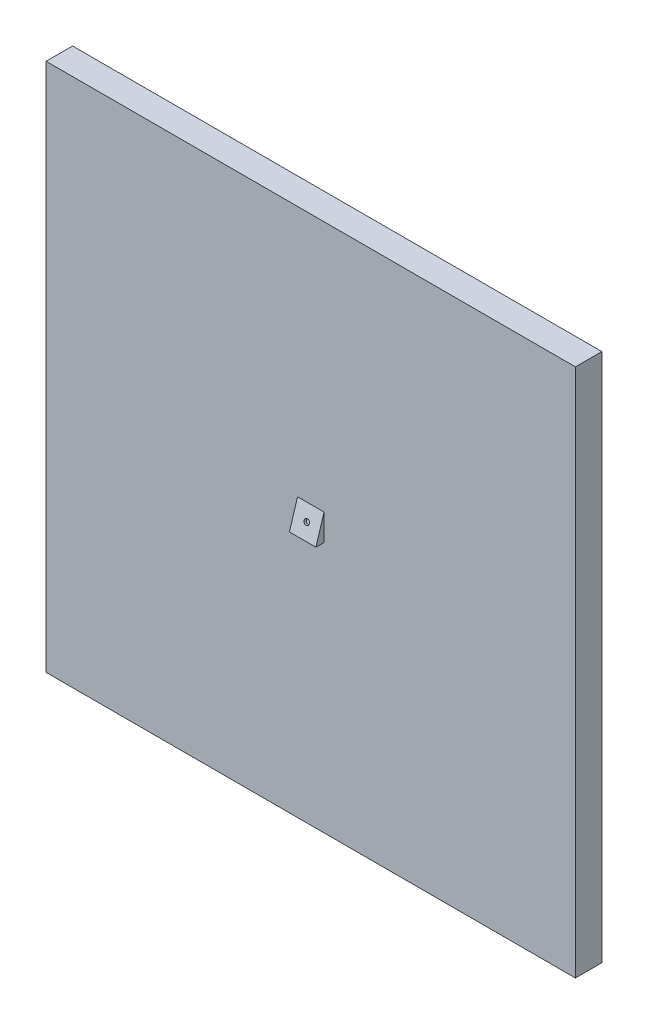
SolidWorks part; units mm, degrees
ref_plane "Ebene vorne" through (0, 0, 0) normal (0, 0, 1) x (1, 0, 0)
ref_plane "Ebene oben" through (0, 0, 0) normal (0, 1, 0) x (1, 0, 0)
ref_plane "Ebene rechts" through (0, 0, 0) normal (1, 0, 0) x (0, 0, -1)
sketch "Skizze1" plane through (0, 0, 0) normal (0, 0, 1) x (1, 0, 0)
  line L1 (-12.5178, 8.125) -> (7.4822, 8.125)
  line L2 (-12.5178, 8.125) -> (-12.5178, -11.875)
  line L3 (-12.5178, -11.875) -> (7.4822, -11.875)
  line L4 (7.4822, 8.125) -> (7.4822, -11.875)
  dimension "D1" = 20
  dimension "D2" = 20
extrude "Aufsatz-Linear austragen1" add sketch "Skizze1" along normal blind 1 contours L2 L1 L4 L3
sketch "Skizze2" plane through (0, 0, 1) normal (0, 0, 1) x (1, 0, 0)
  line L0 (-12.5178, 8.125) -> (7.4822, -11.875) construction
  line L6 (-12.5178, -11.875) -> (7.4822, 8.125) construction
  line L7 (7.4822, 8.125) -> (7.4822, -11.875) construction
  line L9 (-3.0178, -1.375) -> (-2.0178, -1.375)
  line L10 (-3.0178, -1.375) -> (-3.0178, -2.375)
  line L11 (-3.0178, -2.375) -> (-2.0178, -2.375)
  line L12 (-2.0178, -1.375) -> (-2.0178, -2.375)
  dimension "D1" = 1
extrude "Aufsatz-Linear austragen2" add sketch "Skizze2" along normal blind 0.306
sketch "Skizze3" plane through (-3.0178, 0, 0) normal (-1, 0, 0) x (0, 0, 1)
  line L0 (1, -1.375) -> (1.306, -2.375)
  line L1 (1.306, -2.375) -> (1.306, -1.375)
  line L2 (1.306, -1.375) -> (1, -1.375)
extrude "Schnitt-Linear austragen1" cut sketch "Skizze3" against normal blind 10.306 contours L2 L0 L1
sketch "Skizze4" plane through (0, 0.1621, 0.5297) normal (0, 0.2926, 0.9562) x (1, 0, 0)
  line L0 (-3.0178, -1.6074) -> (-2.0178, -2.6532) construction
  line L1 (-3.0178, -2.6532) -> (-2.0178, -1.6074) construction
  circle A0 centre (-2.5178, -2.1303) radius 0.1
extrude "Schnitt-Linear austragen2" cut sketch "Skizze4" against normal blind 0.1
